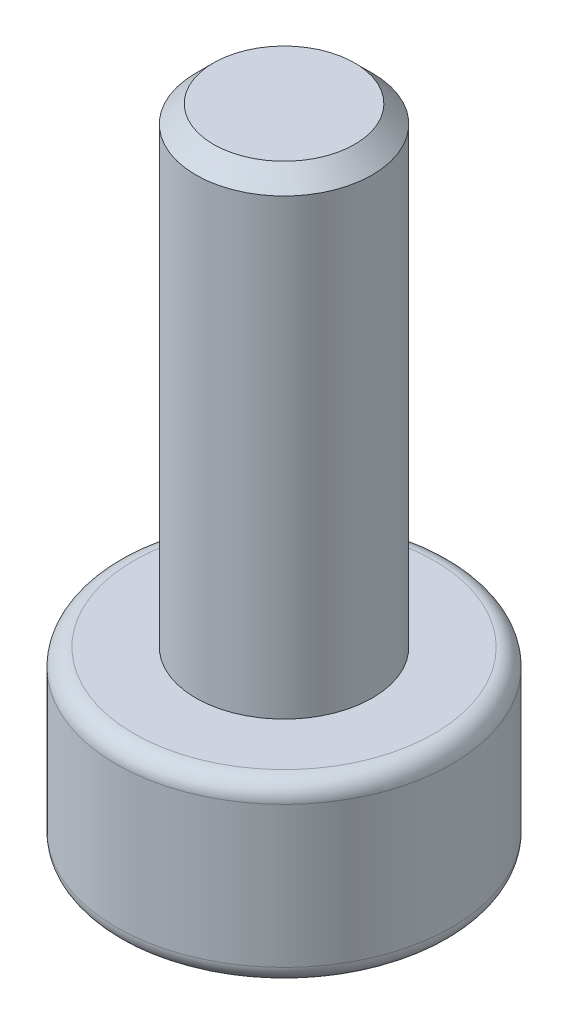
SolidWorks part; units mm, degrees
material "AISI 304"
ref_plane "前视基准面" through (0, 0, 0) normal (0, 0, 1) x (1, 0, 0)
ref_plane "上视基准面" through (0, 0, 0) normal (0, 1, 0) x (1, 0, 0)
ref_plane "右视基准面" through (0, 0, 0) normal (1, 0, 0) x (0, 0, -1)
sketch "草图1" plane through (0, 0, 0) normal (0, 1, 0) x (1, 0, 0)
  circle A0 centre (0, 0) radius 2.85
  dimension "D1" = 5.7
extrude "凸台-拉伸1" add sketch "草图1" along normal blind 3
sketch "草图2" plane through (0, 3, 0) normal (0, 1, 0) x (1, 0, 0)
  circle A0 centre (0, 0) radius 1.5
  dimension "D1" = 3
extrude "凸台-拉伸2" add sketch "草图2" along normal blind 8
sketch "草图3" plane through (0, 0, 0) normal (0, -1, 0) x (1, 0, 0)
  circle A0 centre (0, 0) radius 1.29
  dimension "D1" = 2.58
extrude "切除-拉伸1" cut sketch "草图3" against normal blind 1.3
fillet "圆角1" radius 0.3 2 edges at (0, 3, 2.85) (0, 0, 2.85)
chamfer "倒角1" distance 0.3 angle 45 1 edges at (0, 11, 1.5)
chamfer "倒角2" distance 0.15 angle 45 1 edges at (0, 0, -1.29)
